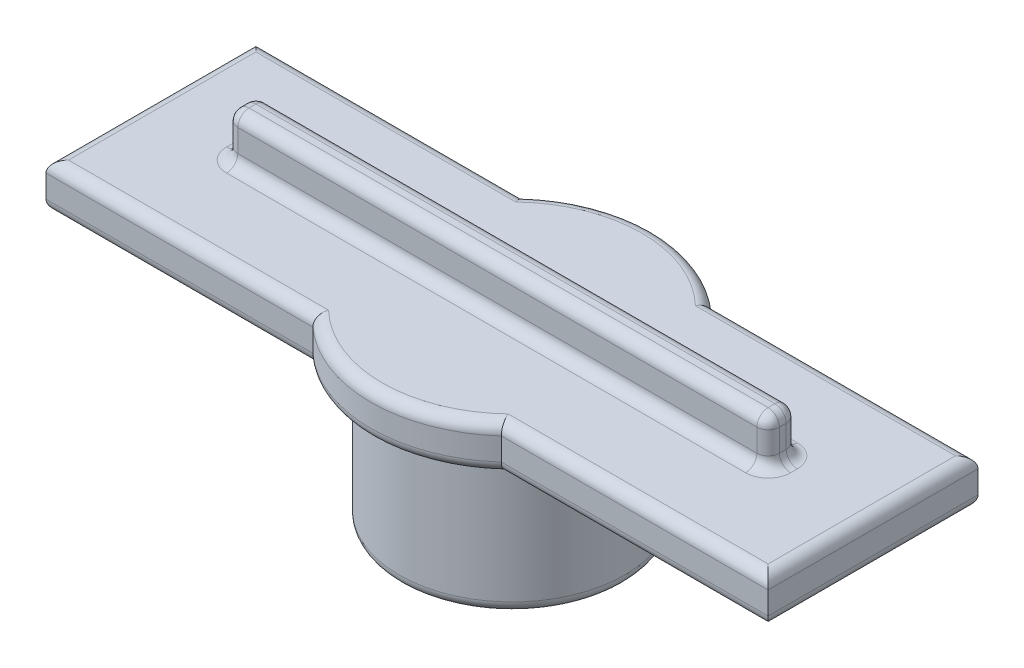
SolidWorks part; units mm, degrees
ref_plane "Front Plane" through (0, 0, 0) normal (0, 0, 1) x (1, 0, 0)
ref_plane "Top Plane" through (0, 0, 0) normal (0, 1, 0) x (1, 0, 0)
ref_plane "Right Plane" through (0, 0, 0) normal (1, 0, 0) x (0, 0, -1)
sketch "Sketch1" plane through (0, 0, 0) normal (0, 1, 0) x (1, 0, 0)
  circle A1 centre (0, 0) radius 12.7
  dimension "D2" = 25.4
extrude "Boss-Extrude1" add sketch "Sketch1" along normal blind 15.875
sketch "Sketch2" plane through (0, 15.875, 0) normal (0, 1, 0) x (1, 0, 0)
  circle A1 centre (0, 0) radius 15.875
  point P1 (-0.3999, 0)
  point P4 (0, 0)
  dimension "D2" = 31.75
extrude "Boss-Extrude2" add sketch "Sketch2" along normal blind 5.08
sketch "Sketch3" plane through (0, 20.955, 0) normal (0, 1, 0) x (1, 0, 0)
  line L1 (-30.48, -1.651) -> (30.48, -1.651)
  line L2 (-30.48, -1.651) -> (-30.48, 1.651)
  line L3 (-30.48, 1.651) -> (30.48, 1.651)
  line L4 (30.48, -1.651) -> (30.48, 1.651)
  line L5 (-30.48, -1.651) -> (30.48, 1.651) construction
  line L6 (-30.48, 1.651) -> (30.48, -1.651) construction
  point P0 (0, 0)
  point P5 (0, 0)
  point P6 (30.9104, 5.8196)
  point P7 (0, 0)
  point P8 (0, 0)
  dimension "D1" = 3.302
  dimension "D2" = 60.96
extrude "Boss-Extrude3" add sketch "Sketch3" along normal blind 5.08
sketch "Sketch4" plane through (0, 20.955, 0) normal (0, -1, 0) x (1, 0, 0)
  line L0 (-15.7889, -1.651) -> (-30.48, -1.651) construction
  line L1 (-40.64, 11.811) -> (40.64, 11.811)
  line L2 (-40.64, 11.811) -> (-40.64, -11.811)
  line L3 (-40.64, -11.811) -> (40.64, -11.811)
  line L4 (40.64, 11.811) -> (40.64, -11.811)
  line L5 (-40.64, 11.811) -> (40.64, -11.811) construction
  line L6 (-40.64, -11.811) -> (40.64, 11.811) construction
  line L7 (-30.48, -1.651) -> (-30.48, 1.651) construction
  point P0 (0, 0)
  dimension "D1" = 10.16
  dimension "D2" = 10.16
extrude "Boss-Extrude4" add sketch "Sketch4" along normal blind 5.08
fillet "Fillet1" radius 1.27 4 edges at (-30.48, 23.495, 1.651) (-30.48, 23.495, -1.651) (30.48, 23.495, -1.651) (30.48, 23.495, 1.651)
fillet "Fillet2" radius 1.27 8 edges at (-30.108, 26.035, 1.279) (-30.48, 26.035, 0) (-30.108, 26.035, -1.279) (0, 26.035, -1.651) (30.108, 26.035, -1.279) (30.48, 26.035, 0) (30.108, 26.035, 1.279) (0, 26.035, 1.651)
fillet "Fillet3" radius 1.27 8 edges at (25.6237, 20.955, 11.811) (0, 20.955, 15.875) (-25.6237, 20.955, 11.811) (-40.64, 20.955, 0) (-25.6237, 20.955, -11.811) (0, 20.955, -15.875) (25.6237, 20.955, -11.811) (40.64, 20.955, 0)
fillet "Fillet4" radius 1.27 8 edges at (-40.64, 15.875, 0) (-25.6237, 15.875, 11.811) (0, 15.875, 15.875) (25.6237, 15.875, 11.811) (40.64, 15.875, 0) (25.6237, 15.875, -11.811) (0, 15.875, -15.875) (-25.6237, 15.875, -11.811)
fillet "Fillet5" radius 1.27 1 edges at (0, 15.875, 12.7)
fillet "Fillet7" radius 1.27 1 edges at (0, 0, 12.7)
fillet "Fillet8" radius 1.27 8 edges at (30.108, 20.955, -1.279) (30.48, 20.955, 0) (30.108, 20.955, 1.279) (0, 20.955, 1.651) (-30.108, 20.955, 1.279) (-30.48, 20.955, 0) (-30.108, 20.955, -1.279) (0, 20.955, -1.651)
sketch "Sketch6" plane through (0, 0, 0) normal (0, -1, 0) x (1, 0, 0)
  circle A0 centre (0, 0) radius 7.8105
  dimension "D1" = 15.621
extrude "Cut-Extrude1" cut sketch "Sketch6" against normal blind 3.175
sketch "Sketch7" plane through (0, 3.175, 0) normal (0, -1, 0) x (1, 0, 0)
  circle A0 centre (0, 0) radius 7.8105
  circle A1 centre (0, 0) radius 7.8105 construction
extrude "Cut-Extrude2" cut sketch "Sketch7" against normal blind 10.795 draft 35.8
